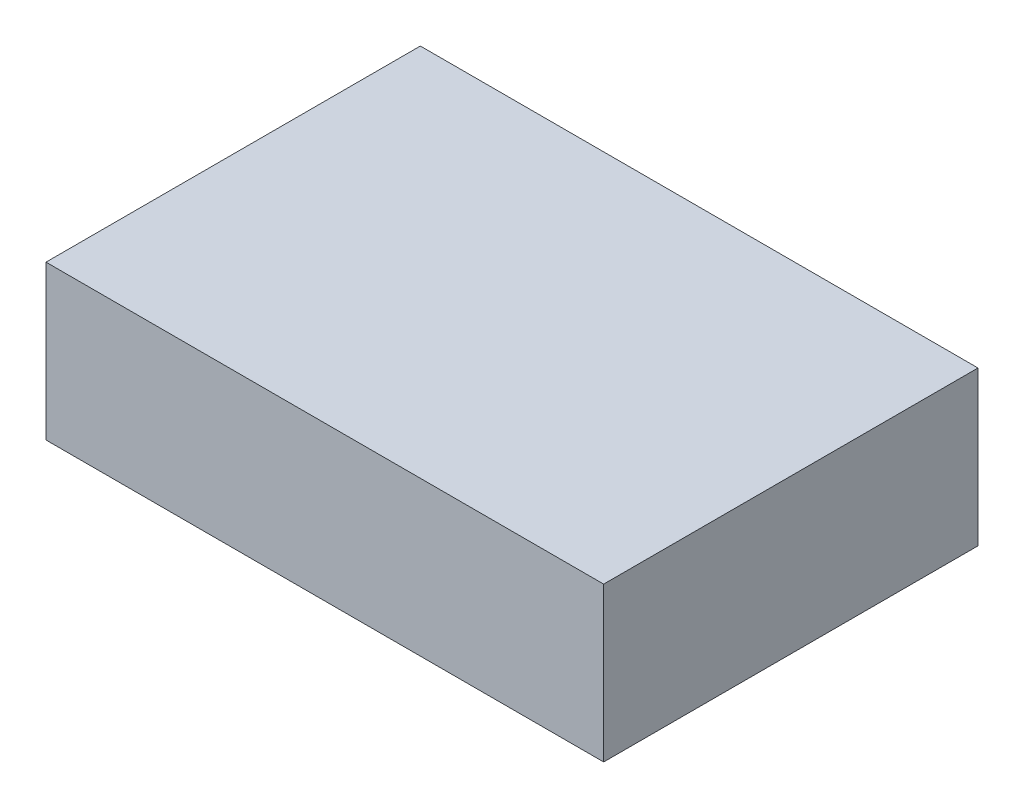
SolidWorks part; units mm, degrees
ref_plane "Front Plane" through (0, 0, 0) normal (0, 0, 1) x (1, 0, 0)
ref_plane "Top Plane" through (0, 0, 0) normal (0, 1, 0) x (1, 0, 0)
ref_plane "Right Plane" through (0, 0, 0) normal (1, 0, 0) x (0, 0, -1)
sketch "Sketch1" plane through (0, 0, 0) normal (0, 1, 0) x (1, 0, 0)
  line L1 (-18.1, -12.15) -> (18.1, -12.15)
  line L2 (-18.1, -12.15) -> (-18.1, 12.15)
  line L3 (-18.1, 12.15) -> (18.1, 12.15)
  line L4 (18.1, -12.15) -> (18.1, 12.15)
  line L5 (-18.1, -12.15) -> (18.1, 12.15) construction
  line L6 (-18.1, 12.15) -> (18.1, -12.15) construction
  point P0 (0, 0)
  dimension "D1" = 36.2
  dimension "D2" = 24.3
extrude "Boss-Extrude1" add sketch "Sketch1" along normal blind 10
